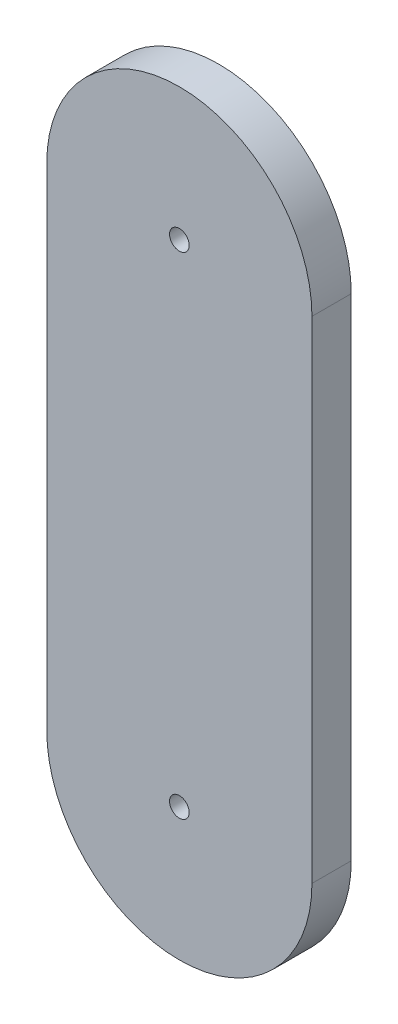
SolidWorks part; units mm, degrees
ref_plane "Front Plane" through (0, 0, 0) normal (0, 0, 1) x (1, 0, 0)
ref_plane "Top Plane" through (0, 0, 0) normal (0, 1, 0) x (1, 0, 0)
ref_plane "Right Plane" through (0, 0, 0) normal (1, 0, 0) x (0, 0, -1)
sketch "Sketch1" plane through (0, 0, 0) normal (0, 0, 1) x (1, 0, 0)
  line L0 (0, 0) -> (0, 250) construction
  line L1 (-67.5, 0) -> (-67.5, 250)
  line L2 (67.5, 0) -> (67.5, 250)
  arc A0 (-67.5, 0) -> (67.5, 0) centre (0, 0) ccw
  arc A1 (67.5, 250) -> (-67.5, 250) centre (0, 250) ccw
  circle A2 centre (0, 250) radius 5
  circle A3 centre (0, 0) radius 5
  point P2 (0, 125)
  dimension "D2" = 67.5
  dimension "D3" = 10
  dimension "D1" = 250
extrude "Boss-Extrude1" add sketch "Sketch1" along normal blind 20
equation "\"Thicknes\"=20"
equation "\"D1@Boss-Extrude1\"=\"Thicknes\""
